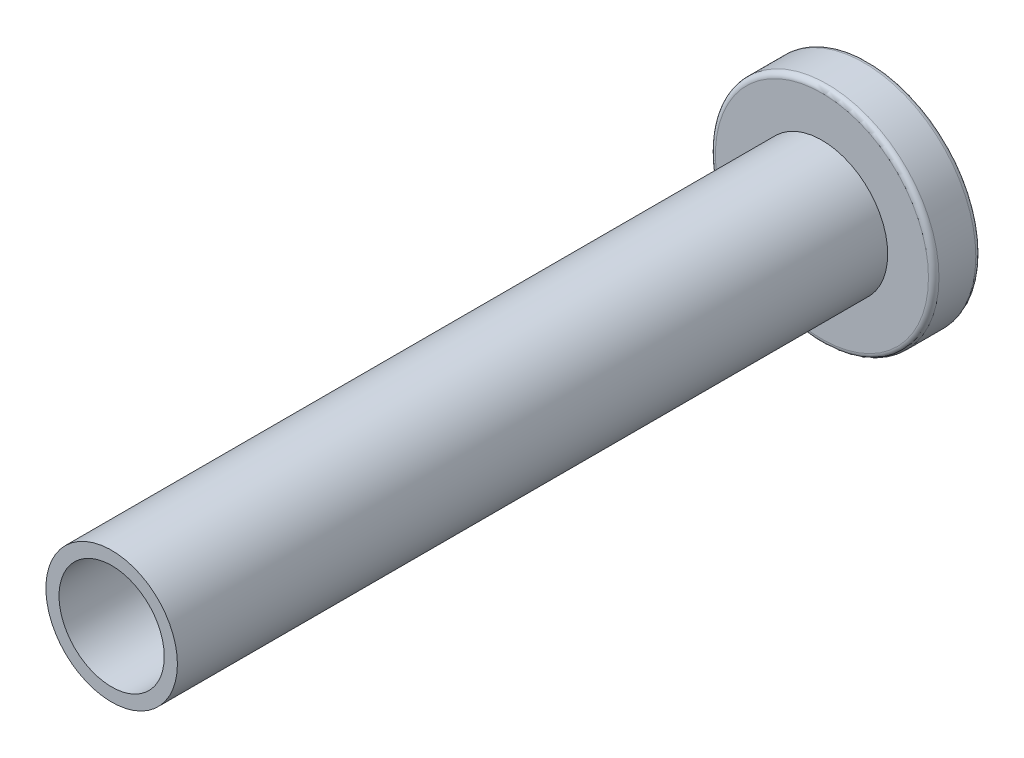
SolidWorks part; units mm, degrees
material "AISI 304"
ref_plane "前视基准面" through (0, 0, 0) normal (0, 0, 1) x (1, 0, 0)
ref_plane "上视基准面" through (0, 0, 0) normal (0, 1, 0) x (1, 0, 0)
ref_plane "右视基准面" through (0, 0, 0) normal (1, 0, 0) x (0, 0, -1)
other "Configuration Table"
sketch "草图1" plane through (0, 0, 0) normal (0, 0, 1) x (1, 0, 0)
  circle A0 centre (0, 0) radius 4.25
  dimension "D1" = 8.5
extrude "凸台-拉伸1" add sketch "草图1" along normal blind 1.8
sketch "草图2" plane through (0, 0, 1.8) normal (0, 0, 1) x (1, 0, 0)
  circle A0 centre (0, 0) radius 2.5
  circle A1 centre (0, 0) radius 2
  dimension "D1" = 5
  dimension "D2" = 4
extrude "凸台-拉伸2" add sketch "草图2" along normal blind 27
fillet "圆角1" radius 0.2 2 edges at (4.25, 0, 0) (4.25, 0, 1.8)
sketch "草图3" plane through (0, 0, 0) normal (0, 0, -1) x (-1, 0, 0)
  line L0 (0, 0) -> (1.4434, 0) construction
  line L1 (1.4434, 0) -> (0.7217, 1.25)
  line L2 (0.7217, 1.25) -> (-0.7217, 1.25)
  line L3 (-0.7217, 1.25) -> (-1.4434, 0)
  line L4 (-1.4434, 0) -> (-0.7217, -1.25)
  line L5 (-0.7217, -1.25) -> (0.7217, -1.25)
  line L6 (0.7217, -1.25) -> (1.4434, 0)
  circle A0 centre (0, 0) radius 1.25 construction
  dimension "D1" = 2.5
extrude "切除-拉伸1" cut sketch "草图3" against normal blind 1.5
